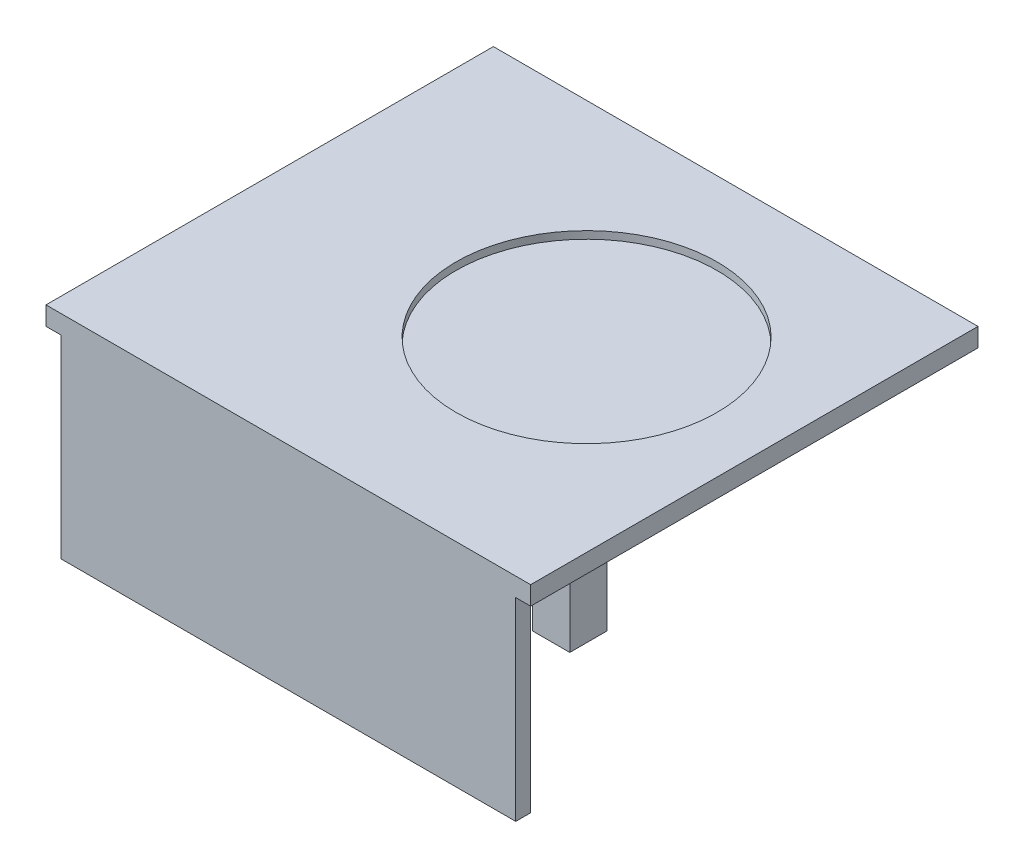
SolidWorks part; units mm, degrees
ref_plane "Front Plane" through (0, 0, 0) normal (0, 0, 1) x (1, 0, 0)
ref_plane "Top Plane" through (0, 0, 0) normal (0, 1, 0) x (1, 0, 0)
ref_plane "Right Plane" through (0, 0, 0) normal (1, 0, 0) x (0, 0, -1)
sketch "Sketch2" plane through (0, 0, 0) normal (0, 1, 0) x (1, 0, 0)
  line L0 (-65, 60) -> (65, 60)
  line L1 (65, 60) -> (65, -60)
  line L2 (65, -60) -> (-65, -60)
  line L3 (-65, -60) -> (-65, 60)
  point P4 (0, 60)
  point P5 (-65, 0)
  dimension "D1" = 130
  dimension "D2" = 120
extrude "Boss-Extrude1" add sketch "Sketch2" along normal blind 5
sketch "Sketch3" plane through (0, 0, 0) normal (0, -1, 0) x (1, 0, 0)
  line L0 (-65, 60) -> (-65, 56)
  line L1 (-65, -60) -> (-65, 60) construction
  line L2 (-65, 56) -> (61, 56)
  line L3 (61, 56) -> (61, 60)
  line L4 (-65, 60) -> (65, 60) construction
  line L5 (61, 60) -> (-65, 60)
  line L6 (65, 60) -> (65, -60) construction
  dimension "D1" = 4
  dimension "D2" = 4
extrude "Boss-Extrude2" add sketch "Sketch3" along normal blind 52
sketch "Sketch5" plane through (0, 5, 0) normal (0, 1, 0) x (1, 0, 0)
  line L0 (-65, 60) -> (-65, -60) construction
  line L1 (65, 60) -> (-65, 60) construction
  circle A0 centre (15, 5) radius 35
  dimension "D1" = 70
  dimension "D2" = 80
  dimension "D3" = 55
extrude "Cut-Extrude1" cut sketch "Sketch5" against normal blind 2
sketch "Sketch7" plane through (0, 0, 0) normal (0, -1, 0) x (1, 0, 0)
  line L0 (-61, 45.5) -> (-51, 45.5)
  line L2 (-51, 45.5) -> (-51, 35.5)
  line L3 (-51, 35.5) -> (-61, 35.5)
  line L4 (-61, 35.5) -> (-61, 45.5)
  line L5 (-65, 56) -> (61, 56) construction
  line L6 (61, 45.5) -> (51, 45.5)
  line L7 (51, 45.5) -> (51, 35.5)
  line L8 (51, 35.5) -> (61, 35.5)
  line L9 (61, 35.5) -> (61, 45.5)
  line L10 (65, 60) -> (65, -60) construction
  line L11 (-65, -60) -> (-65, 56) construction
  dimension "D1" = 10
  dimension "D2" = 10
  dimension "D3" = 10.5
  dimension "D4" = 10
  dimension "D5" = 10
  dimension "D6" = 4
  dimension "D7" = 4
extrude "Boss-Extrude3" add sketch "Sketch7" along normal blind 20
sketch "Sketch9" plane through (0, 0, 56) normal (0, 0, -1) x (-1, 0, 0)
  line L0 (65, 0) -> (61, 0)
  line L1 (65, 0) -> (-61, 0) construction
  line L2 (61, 0) -> (61, -52)
  line L3 (65, -52) -> (-61, -52) construction
  line L4 (61, -52) -> (65, -52)
  line L5 (65, -52) -> (65, 0)
  dimension "D1" = 4
extrude "Cut-Extrude2" cut sketch "Sketch9" against normal blind 5
